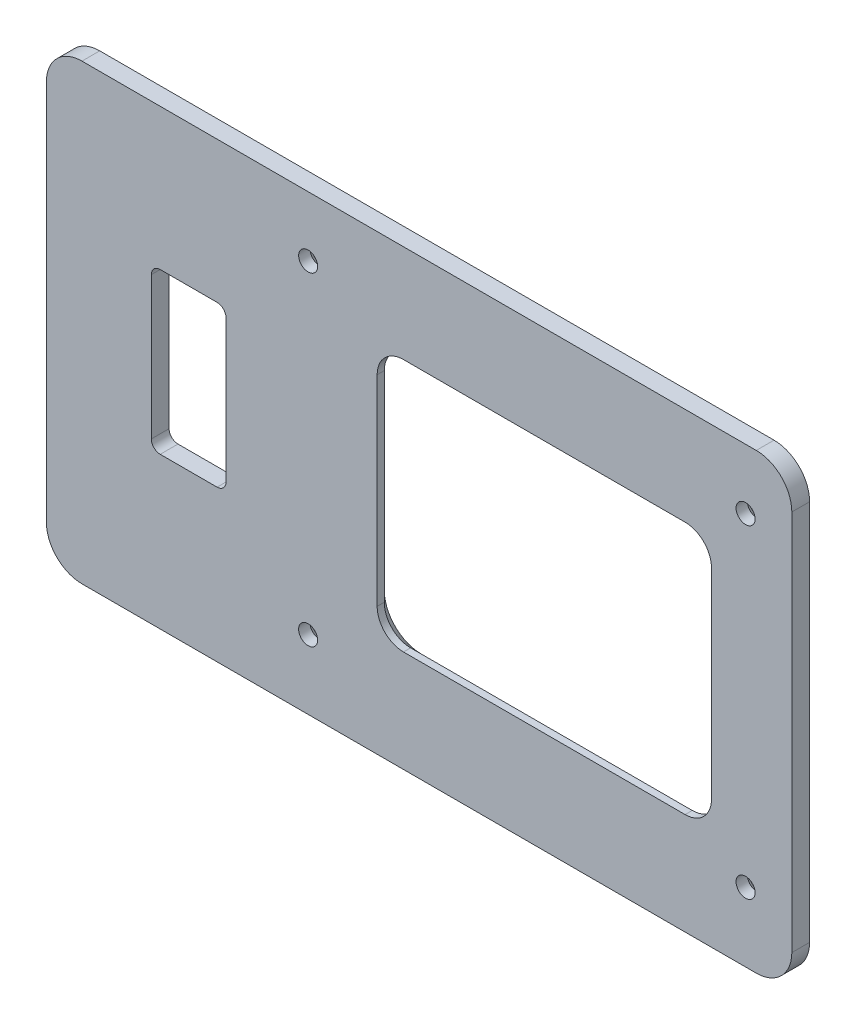
SolidWorks part; units mm, degrees
ref_plane "Front Plane" through (0, 0, 0) normal (0, 0, 1) x (1, 0, 0)
ref_plane "Top Plane" through (0, 0, 0) normal (0, 1, 0) x (1, 0, 0)
ref_plane "Right Plane" through (0, 0, 0) normal (1, 0, 0) x (0, 0, -1)
sketch "Sketch1" plane through (0, 0, 0) normal (0, 0, 1) x (1, 0, 0)
  line L0 (-151.9669, 98.7552) -> (-151.9669, -98.7552) construction
  line L1 (-135.4569, -115.2652) -> (135.4569, -115.2652) construction
  line L2 (151.9669, -98.7552) -> (151.9669, 98.7552) construction
  line L3 (135.4569, 115.2652) -> (-135.4569, 115.2652) construction
  line L4 (0, 115.2652) -> (0, 0) construction
  line L5 (0, 0) -> (151.9669, 0) construction
  line L25 (-151.9669, 98.7552) -> (-151.9669, -98.7552)
  line L27 (-135.4569, -115.2652) -> (135.4569, -115.2652)
  line L29 (151.9669, -98.7552) -> (151.9669, 98.7552)
  line L31 (135.4569, 115.2652) -> (-135.4569, 115.2652)
  arc A0 (-135.4569, -115.2652) -> (-151.9669, -98.7552) centre (-135.4569, -98.7552) cw
  arc A1 (135.4569, -115.2652) -> (151.9669, -98.7552) centre (135.4569, -98.7552) ccw
  arc A2 (151.9669, 98.7552) -> (135.4569, 115.2652) centre (135.4569, 98.7552) ccw
  arc A3 (-151.9669, 98.7552) -> (-135.4569, 115.2652) centre (-135.4569, 98.7552) cw
  arc A4 (-135.4569, -115.2652) -> (-151.9669, -98.7552) centre (-135.4569, -98.7552) cw construction
  arc A5 (135.4569, -115.2652) -> (151.9669, -98.7552) centre (135.4569, -98.7552) ccw construction
  arc A6 (151.9669, 98.7552) -> (135.4569, 115.2652) centre (135.4569, 98.7552) ccw construction
  arc A7 (-151.9669, 98.7552) -> (-135.4569, 115.2652) centre (-135.4569, 98.7552) cw construction
  dimension "D1" = 16.51
  dimension "D3" = 230.5304
  dimension "D4" = 303.9339
  dimension "D2" = 0
extrude "Boss-Extrude1" add sketch "Sketch1" against normal blind 3.175
hole_wizard "#6 Clearance Hole1" positions "Sketch2" profile "Sketch3" hole size "#6" standard "ANSI Inch" end condition up to next
sketch "Sketch2" plane through (0, 0, 0) normal (0, 0, 1) x (1, 0, 0)
  line L3 (140.9687, 63.5) -> (140.9687, -63.5) construction
  line L6 (-101.092, 104.648) -> (101.092, 104.648) construction
  line L9 (-140.9687, 63.5) -> (-140.9687, -63.5) construction
  line L10 (-101.092, -104.648) -> (101.092, -104.648) construction
  line L13 (0, -104.648) -> (0, 0) construction
  line L14 (0, 0) -> (140.9687, 0) construction
  line L17 (0, 104.648) -> (0, 0) construction
  line L18 (0, 0) -> (-140.9687, 0) construction
  point P38 (101.092, 104.648)
  point P40 (-101.092, 104.648)
  point P42 (-140.9687, 63.5)
  point P44 (-140.9687, -63.5)
  point P48 (101.092, -104.648)
  point P50 (140.9687, -63.5)
  point P52 (140.9687, 63.5)
  point P108 (-101.092, -104.648)
  point P117 (0, -104.648)
  point P125 (0, 104.648)
  dimension "D1" = 104.648
  dimension "D2" = 140.9687
  dimension "D3" = 104.648
  dimension "D4" = 140.9687
  dimension "D5" = 127
  dimension "D6" = 127
  dimension "D7" = 202.184
  dimension "D8" = 202.184
sketch "Sketch3" plane through (101.092, 104.648, 0) normal (1, 0, 0) x (0, -1, 0)
  line L0 (0, 0) -> (0, 3.175)
  line L1 (0, 3.175) -> (3.3655, 3.175)
  line L2 (2.1526, 2.1573) -> (2.1526, 0)
  line L5 (2.1526, 0) -> (0, 0)
  line L7 (3.3655, 3.175) -> (2.1526, 2.1573)
  line L8 (-3.3655, 3.175) -> (-2.1527, 2.1573) construction
  line L11 (0, -6.35) -> (0, 107.95) construction
  dimension "Thru Hole Dia." = 4.3053
  dimension "Thru Hole Depth" = 3.175
  dimension "Far C'Sink Dia." = 6.731
  dimension "Far C'Sink Angle" = 100
sketch "Sketch23" plane through (0, 0, 0) normal (0, 0, 1) x (1, 0, 0)
  line L0 (135.4569, 115.2652) -> (-135.4569, 115.2652) construction
  line L1 (151.9669, -98.7552) -> (151.9669, 98.7552) construction
  circle A0 centre (104.2657, 42.164) radius 24.765
  dimension "D1" = 49.53
  dimension "D2" = 73.1012
  dimension "D3" = 47.7012
extrude "Cut-Extrude10" cut sketch "Sketch23" against normal through all
sketch "Sketch24" plane through (0, 0, 0) normal (0, 0, 1) x (1, 0, 0)
  line L1 (-92.9119, 38.9204) -> (-33.2219, 38.9204)
  line L2 (-92.9119, 38.9204) -> (-92.9119, -6.2916)
  line L3 (-92.9119, -6.2916) -> (-33.2219, -6.2916)
  line L4 (-33.2219, 38.9204) -> (-33.2219, -6.2916)
  line L5 (-92.9119, 38.9204) -> (-33.2219, -6.2916) construction
  line L7 (-151.9669, 98.7552) -> (-151.9669, -98.7552) construction
  line L8 (-135.4569, -115.2652) -> (135.4569, -115.2652) construction
  point P4 (-63.0669, 16.3144)
  dimension "D1" = 88.9
  dimension "D2" = 131.5796
  dimension "D3" = 59.69
  dimension "D4" = 45.212
extrude "Cut-Extrude11" cut sketch "Sketch24" against normal through all
fillet "Fillet2" radius 4.699 4 edges at (-33.2219, -6.2916, -1.5875) (-92.9119, -6.2916, -1.5875) (-92.9119, 38.9204, -1.5875) (-33.2219, 38.9204, -1.5875)
chamfer "Chamfer1" distance 1.905 angle 45 8 edges at (-63.0669, -6.2916, -3.175) (-92.9119, 16.3144, -3.175) (-63.0669, 38.9204, -3.175) (-33.2219, 16.3144, -3.175) (-91.5356, -4.9153, -3.175) (-91.5356, 37.5441, -3.175) (-34.5982, -4.9153, -3.175) (-34.5982, 37.5441, -3.175)
hole_wizard "M3 Clearance Hole3" positions "Sketch29" profile "Sketch30" hole size "M3" standard "ANSI Metric" end condition up to next
sketch "Sketch29" plane through (0, 0, 0) normal (0, 0, 1) x (1, 0, 0)
  line L1 (79.57, 66.8597) -> (128.9614, 66.8597) construction
  line L2 (79.57, 66.8597) -> (79.57, 17.4683) construction
  line L3 (79.57, 17.4683) -> (128.9614, 17.4683) construction
  line L4 (128.9614, 66.8597) -> (128.9614, 17.4683) construction
  line L5 (104.2657, 66.8597) -> (104.2657, 17.4683) construction
  circle A2 centre (104.2657, 42.164) radius 34.925
  circle A3 centre (104.2657, 42.164) radius 24.765 construction
  point P0 (79.57, 66.8597)
  point P2 (128.9614, 66.8597)
  point P4 (128.9614, 17.4683)
  point P6 (79.57, 17.4683)
  dimension "D1" = 69.85
sketch "Sketch30" plane through (79.57, 66.8597, 0) normal (1, 0, 0) x (0, -1, 0)
  line L0 (0, 0) -> (0, 3.175)
  line L1 (0, 3.175) -> (2.85, 3.175)
  line L2 (1.8, 2.125) -> (1.8, 0)
  line L5 (1.8, 0) -> (0, 0)
  line L7 (2.85, 3.175) -> (1.8, 2.125)
  line L8 (-2.85, 3.175) -> (-1.8, 2.125) construction
  line L11 (0, -6.35) -> (0, 107.95) construction
  dimension "Thru Hole Dia." = 3.6
  dimension "Thru Hole Depth" = 3.175
  dimension "Far C'Sink Dia." = 5.7
  dimension "Far C'Sink Angle" = 90
hole_wizard "M3 Clearance Hole1" positions "Sketch31" profile "Sketch32" hole size "M3" standard "ANSI Metric" end condition up to next
sketch "Sketch31" plane through (0, 0, -3.175) normal (0, 0, -1) x (-1, 0, 0)
  line L1 (17.6769, -38.5952) -> (117.6769, -38.5952) construction
  line L2 (17.6769, -38.5952) -> (17.6769, -88.5952) construction
  line L3 (17.6769, -88.5952) -> (117.6769, -88.5952) construction
  line L4 (117.6769, -38.5952) -> (117.6769, -88.5952) construction
  line L5 (151.9669, 98.7552) -> (151.9669, -98.7552) construction
  line L6 (135.4569, -115.2652) -> (-135.4569, -115.2652) construction
  point P0 (17.6769, -38.5952)
  point P2 (117.6769, -38.5952)
  point P4 (117.6769, -88.5952)
  point P6 (17.6769, -88.5952)
  dimension "D1" = 100
  dimension "D2" = 50
  dimension "D3" = 34.29
  dimension "D4" = 26.67
sketch "Sketch32" plane through (-17.6769, -38.5952, -3.175) normal (1, 0, 0) x (0, 1, 0)
  line L0 (0, 0) -> (0, 3.175)
  line L1 (0, 3.175) -> (1.8, 3.175)
  line L2 (1.8, 3.175) -> (1.8, 1.05)
  line L3 (1.8, 1.05) -> (2.85, 0)
  line L5 (2.85, 0) -> (0, 0)
  line L6 (-1.8, 1.05) -> (-2.85, 0) construction
  line L11 (0, -6.35) -> (0, 107.95) construction
  dimension "Thru Hole Dia." = 3.6
  dimension "Thru Hole Depth" = 3.175
  dimension "Near C'Sink Dia." = 5.7
  dimension "Near C'Sink Angle" = 90
hole_wizard "M3 Clearance Hole2" positions "Sketch33" profile "Sketch34" hole size "M3" standard "ANSI Metric" end condition up to next
sketch "Sketch33" plane through (0, 0, 0) normal (0, 0, 1) x (1, 0, 0)
  line L0 (-135.4569, -115.2652) -> (135.4569, -115.2652) construction
  line L1 (151.9669, -98.7552) -> (151.9669, 98.7552) construction
  line L2 (25.2519, -75.5297) -> (81.9523, -75.5297) construction
  line L4 (127.0876, -35.9197) -> (127.0876, -81.4197) construction
  line L5 (127.0876, -35.9197) -> (90.5876, -35.9197) construction
  line L6 (90.5876, -35.9197) -> (90.5876, -81.4197) construction
  line L7 (90.5876, -81.4197) -> (127.0876, -81.4197) construction
  line L8 (32.6019, -49.1297) -> (74.6023, -49.1297) construction
  line L11 (53.6021, -49.1297) -> (53.6021, -75.5297) construction
  point P0 (25.2519, -75.5297)
  point P7 (81.9523, -75.5297)
  point P15 (127.0876, -81.4197)
  point P18 (127.0876, -35.9197)
  point P23 (90.5876, -81.4197)
  point P25 (90.5876, -35.9197)
  point P33 (32.6019, -49.1297)
  point P35 (74.6023, -49.1297)
  dimension "D1" = 5.89
  dimension "D2" = 26.4
  dimension "D3" = 56.7004
  dimension "D4" = 24.8793
  dimension "D5" = 33.8455
  dimension "D6" = 45.5
  dimension "D7" = 36.5
  dimension "D8" = 7.35
  dimension "D9" = 8.6353
sketch "Sketch34" plane through (25.2519, -75.5297, 0) normal (1, 0, 0) x (0, -1, 0)
  line L0 (0, 0) -> (0, 3.175)
  line L1 (0, 3.175) -> (2.85, 3.175)
  line L2 (1.8, 2.125) -> (1.8, 0)
  line L5 (1.8, 0) -> (0, 0)
  line L7 (2.85, 3.175) -> (1.8, 2.125)
  line L8 (-2.85, 3.175) -> (-1.8, 2.125) construction
  line L11 (0, -6.35) -> (0, 107.95) construction
  dimension "Thru Hole Dia." = 3.6
  dimension "Thru Hole Depth" = 3.175
  dimension "Far C'Sink Dia." = 5.7
  dimension "Far C'Sink Angle" = 90
sketch "Sketch35" plane through (0, 0, 0) normal (0, 0, 1) x (1, 0, 0)
  line L1 (-133.2344, 31.1277) -> (-119.8994, 31.1277)
  line L2 (-133.2344, 31.1277) -> (-133.2344, 2.5527)
  line L3 (-133.2344, 2.5527) -> (-119.8994, 2.5527)
  line L4 (-119.8994, 31.1277) -> (-119.8994, 2.5527)
  line L6 (-133.2344, 31.1277) -> (-119.8994, 2.5527) construction
  line L7 (-151.9669, 98.7552) -> (-151.9669, -98.7552) construction
  line L8 (135.4569, 115.2652) -> (-135.4569, 115.2652) construction
  point P4 (-126.5669, 16.8402)
  dimension "D1" = 13.335
  dimension "D2" = 28.575
  dimension "D3" = 25.4
  dimension "D4" = 98.425
extrude "Cut-Extrude12" cut sketch "Sketch35" against normal through all
fillet "Fillet1" radius 1.5875 4 edges at (-119.8994, 31.1277, -1.5875) (-119.8994, 2.5527, -1.5875) (-133.2344, 2.5527, -1.5875) (-133.2344, 31.1277, -1.5875)
hole_wizard "Ø8.0mm Dowel Hole1" positions "Sketch36" profile "Sketch37" hole size "Ø8.0" standard "ANSI Metric" end condition up to next
sketch "Sketch36" plane through (0, 0, -3.175) normal (0, 0, -1) x (-1, 0, 0)
  line L0 (31.3169, 16.3144) -> (12.2669, 16.3144) construction
  line L1 (31.3169, -1.5926) -> (31.3169, 34.2214) construction
  line L4 (12.2669, 29.0144) -> (12.2669, 3.6144) construction
  point P7 (12.2669, 29.0144)
  point P8 (12.2669, 3.6144)
  point P11 (12.2669, 16.3144)
  dimension "D1" = 25.4
  dimension "D2" = 19.05
sketch "Sketch37" plane through (-12.2669, 3.6144, -3.175) normal (1, 0, 0) x (0, 1, 0)
  line L0 (0, 0) -> (0, 3.175)
  line L1 (0, 3.175) -> (4, 3.175)
  line L2 (4, 3.175) -> (4, 0)
  line L5 (4, 0) -> (0, 0)
  line L11 (0, -6.35) -> (0, 107.95) construction
  dimension "Thru Hole Dia." = 8
  dimension "Thru Hole Depth" = 3.175
hole_wizard "M3 Clearance Hole4" positions "Sketch38" profile "Sketch39" hole size "M3" standard "ANSI Metric" end condition through all
sketch "Sketch38" plane through (0, 0, 0) normal (0, 0, 1) x (1, 0, 0)
  line L16 (-105.2309, 45.6514) -> (-27.1259, 45.6514) construction
  line L17 (-105.2309, 45.6514) -> (-105.2309, -12.1336) construction
  line L18 (-105.2309, -12.1336) -> (-27.1259, -12.1336) construction
  line L19 (-27.1259, 45.6514) -> (-27.1259, -12.1336) construction
  line L26 (-33.2219, -1.5926) -> (-33.2219, 34.2214) construction
  line L27 (-37.9209, 38.9204) -> (-88.2129, 38.9204) construction
  point P0 (-105.2309, 45.6514)
  point P2 (-27.1259, 45.6514)
  point P4 (-27.1259, -12.1336)
  point P6 (-105.2309, -12.1336)
  dimension "D1" = 78.105
  dimension "D2" = 57.785
  dimension "D3" = 6.096
  dimension "D4" = 6.731
sketch "Sketch39" plane through (-105.2309, 45.6514, 0) normal (1, 0, 0) x (0, -1, 0)
  line L0 (0, 0) -> (0, 3.175)
  line L1 (0, 3.175) -> (2.85, 3.175)
  line L2 (1.7, 2.025) -> (1.7, 0)
  line L5 (1.7, 0) -> (0, 0)
  line L7 (2.85, 3.175) -> (1.7, 2.025)
  line L8 (-2.85, 3.175) -> (-1.7, 2.025) construction
  line L11 (0, -6.35) -> (0, 107.95) construction
  dimension "Thru Hole Dia." = 3.4
  dimension "Thru Hole Depth" = 3.175
  dimension "Far C'Sink Dia." = 5.7
  dimension "Far C'Sink Angle" = 90
sketch "Sketch40" plane through (0, 0, -3.175) normal (0, 0, -1) x (-1, 0, 0)
  line L0 (94.8169, 34.2214) -> (94.8169, -1.5926) construction
  line L1 (88.2129, -8.1966) -> (37.9209, -8.1966) construction
  line L2 (31.3169, -1.5926) -> (31.3169, 34.2214) construction
  line L3 (37.9209, 40.8254) -> (88.2129, 40.8254) construction
  line L4 (94.8169, 34.2214) -> (94.8169, -1.5926)
  line L5 (88.2129, -8.1966) -> (37.9209, -8.1966)
  line L6 (31.3169, -1.5926) -> (31.3169, 34.2214)
  line L7 (37.9209, 40.8254) -> (88.2129, 40.8254)
  arc A0 (94.8169, 34.2214) -> (88.2129, 40.8254) centre (88.2129, 34.2214) ccw construction
  arc A1 (88.2129, -8.1966) -> (94.8169, -1.5926) centre (88.2129, -1.5926) ccw construction
  arc A2 (31.3169, -1.5926) -> (37.9209, -8.1966) centre (37.9209, -1.5926) ccw construction
  arc A3 (37.9209, 40.8254) -> (31.3169, 34.2214) centre (37.9209, 34.2214) ccw construction
  arc A4 (94.8169, 34.2214) -> (88.2129, 40.8254) centre (88.2129, 34.2214) ccw
  arc A5 (88.2129, -8.1966) -> (94.8169, -1.5926) centre (88.2129, -1.5926) ccw
  arc A6 (31.3169, -1.5926) -> (37.9209, -8.1966) centre (37.9209, -1.5926) ccw
  arc A7 (37.9209, 40.8254) -> (31.3169, 34.2214) centre (37.9209, 34.2214) ccw
  dimension "D3" = 6.604
  dimension "D1" = 49.022
  dimension "D2" = 63.5
sketch "Sketch42" plane through (0, 0, -3.175) normal (0, 0, -1) x (-1, 0, 0)
  line L0 (151.9669, 98.7552) -> (151.9669, -98.7552) construction
  line L1 (18.8705, 56.3683) -> (151.9669, 56.3683)
  line L2 (18.8705, 56.3683) -> (18.8705, -24.4645)
  line L3 (18.8705, -24.4645) -> (151.9669, -24.4645)
  line L4 (151.9669, 56.3683) -> (151.9669, -24.4645)
extrude "Cut-Extrude13" cut sketch "Sketch42" against normal through all flip side to cut
fillet "Fillet3" radius 6.35 4 edges at (-151.9669, 56.3683, -1.5875) (-151.9669, -24.4645, -1.5875) (-18.8705, -24.4645, -1.5875) (-18.8705, 56.3683, -1.5875)
